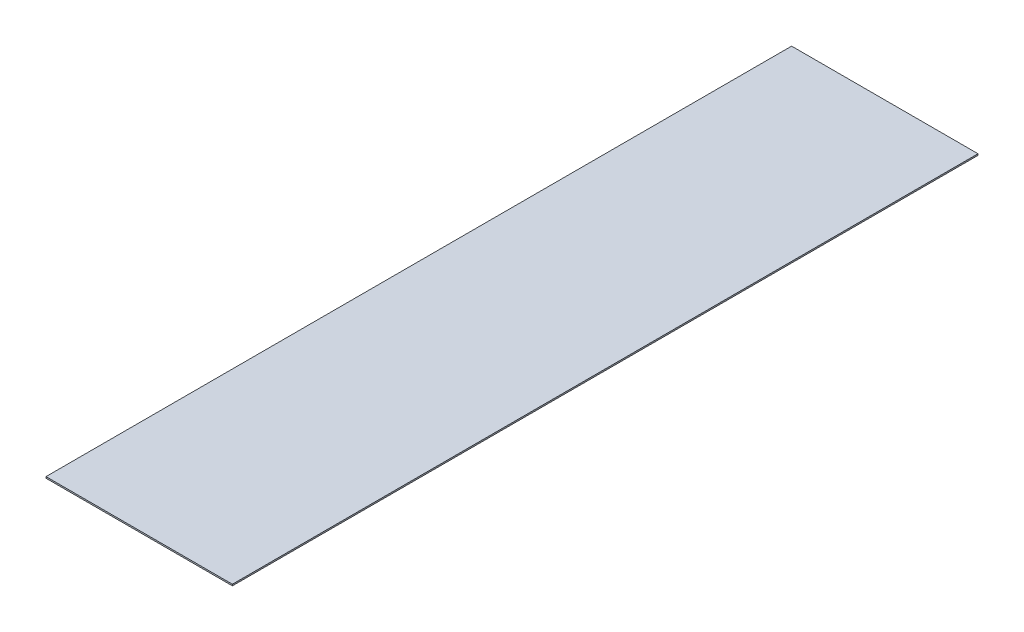
SolidWorks part; units mm, degrees
material "E-Glass Fiber"
ref_plane "Front Plane" through (0, 0, 0) normal (0, 0, 1) x (1, 0, 0)
ref_plane "Top Plane" through (0, 0, 0) normal (0, 1, 0) x (1, 0, 0)
ref_plane "Right Plane" through (0, 0, 0) normal (1, 0, 0) x (0, 0, -1)
sketch "Sketch1" plane through (0, 0, 0) normal (0, 0, 1) x (1, 0, 0)
  line L1 (-63.5, -0.5) -> (63.5, -0.5)
  line L2 (-63.5, -0.5) -> (-63.5, 0.5)
  line L3 (-63.5, 0.5) -> (63.5, 0.5)
  line L4 (63.5, -0.5) -> (63.5, 0.5)
  line L5 (-63.5, -0.5) -> (63.5, 0.5) construction
  line L6 (-63.5, 0.5) -> (63.5, -0.5) construction
  point P0 (0, 0)
  dimension "D1" = 1
  dimension "D2" = 127
extrude "Boss-Extrude1" add sketch "Sketch1" against normal blind 508
